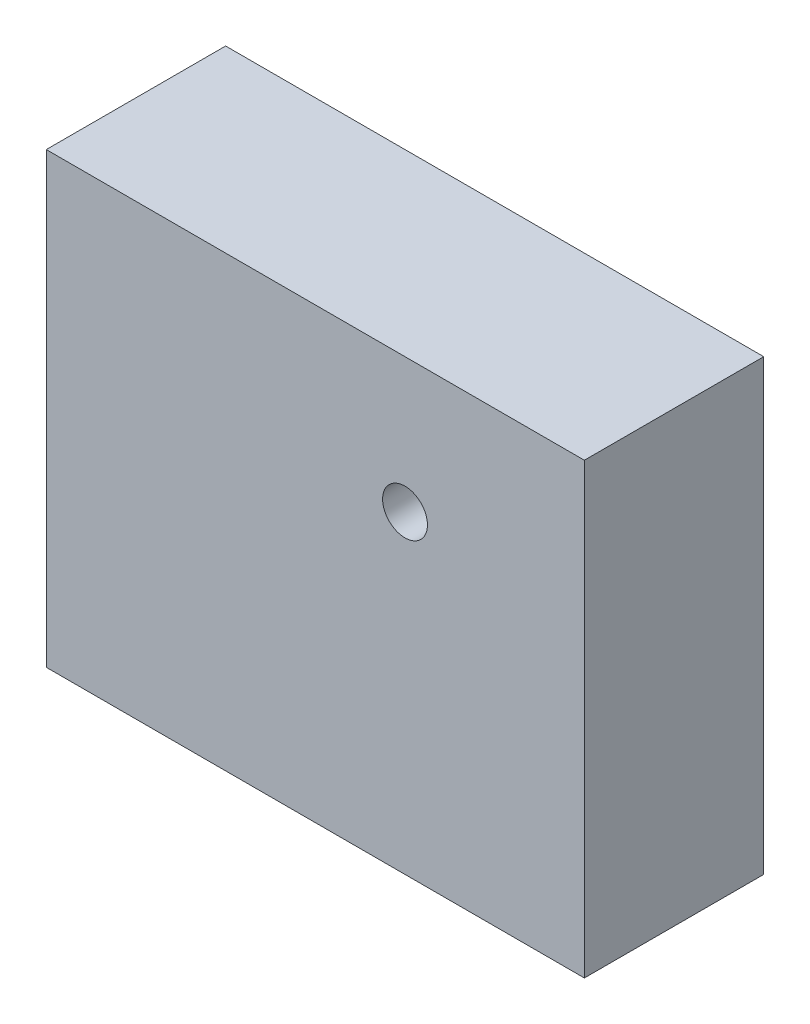
SolidWorks part; units mm, degrees
material "1.0038 (S235JRG2)"
ref_plane "Ebene vorne" through (0, 0, 0) normal (0, 0, 1) x (1, 0, 0)
ref_plane "Ebene oben" through (0, 0, 0) normal (0, 1, 0) x (1, 0, 0)
ref_plane "Ebene rechts" through (0, 0, 0) normal (1, 0, 0) x (0, 0, -1)
sketch "Skizze1" plane through (0, 0, 0) normal (0, 0, 1) x (1, 0, 0)
  line L1 (-30, -25) -> (30, -25)
  line L2 (-30, -25) -> (-30, 25)
  line L3 (-30, 25) -> (30, 25)
  line L4 (30, -25) -> (30, 25)
  dimension "D1" = 60
  dimension "D2" = 50
  dimension "D3" = 30
  dimension "D4" = 25
extrude "Aufsatz-Linear austragen1" add sketch "Skizze1" along normal blind 20
sketch "Skizze2" plane through (0, 0, 20) normal (0, 0, 1) x (1, 0, 0)
  circle A0 centre (10, 10) radius 2.5
  dimension "D1" = 5
  dimension "D2" = 10
  dimension "D3" = 10
extrude "Schnitt-Linear austragen1" cut sketch "Skizze2" against normal blind 12
equation "\"L\" = 60"
equation "\"D1@Skizze1\" = \"L\""
